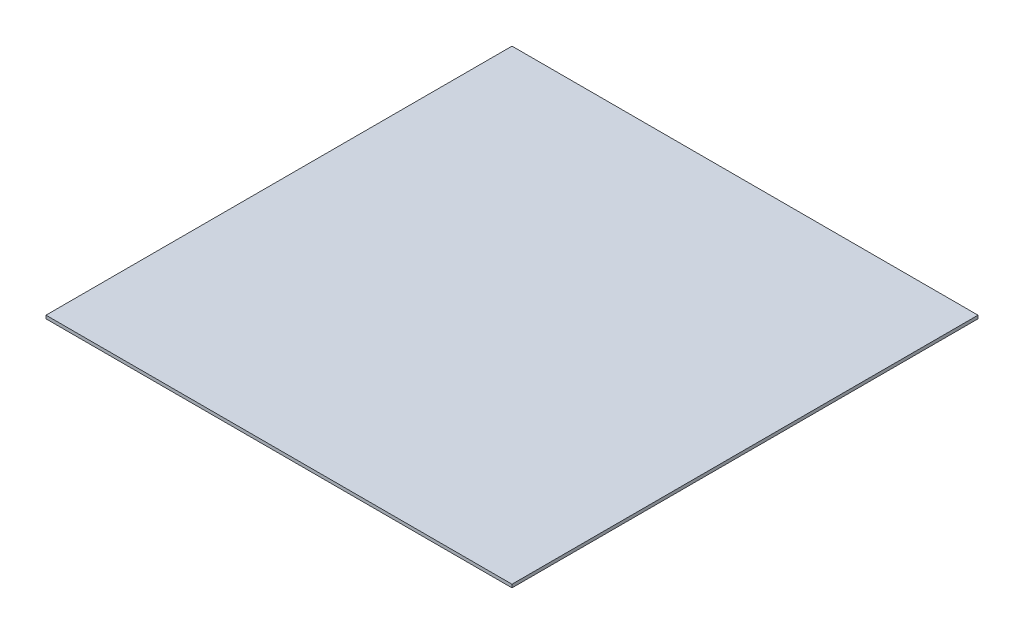
SolidWorks part; units mm, degrees
material "Nylon 6/10"
ref_plane "Front Plane" through (0, 0, 0) normal (0, 0, 1) x (1, 0, 0)
ref_plane "Top Plane" through (0, 0, 0) normal (0, 1, 0) x (1, 0, 0)
ref_plane "Right Plane" through (0, 0, 0) normal (1, 0, 0) x (0, 0, -1)
sketch "Sketch1" plane through (0, 0, 0) normal (0, 1, 0) x (1, 0, 0)
  line L1 (-15, 15) -> (15, 15)
  line L2 (-15, 15) -> (-15, -15)
  line L3 (-15, -15) -> (15, -15)
  line L4 (15, 15) -> (15, -15)
  line L5 (-15, 15) -> (15, -15) construction
  line L6 (-15, -15) -> (15, 15) construction
  point P0 (0, 0)
  dimension "D1" = 30
  dimension "D2" = 30
extrude "Boss-Extrude1" add sketch "Sketch1" along normal blind 0.206
